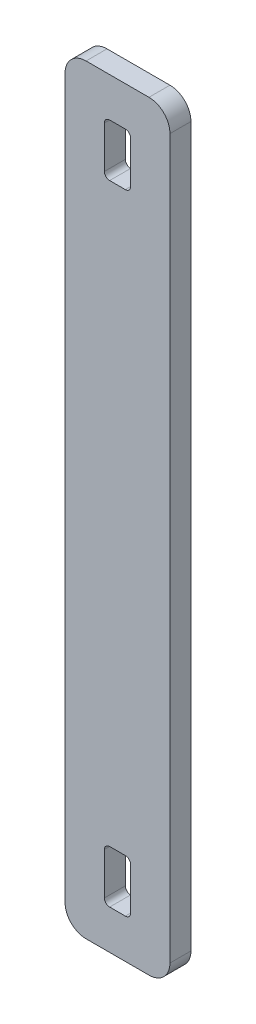
SolidWorks part; units mm, degrees
ref_plane "Plan de face" through (0, 0, 0) normal (0, 0, 1) x (1, 0, 0)
ref_plane "Plan de dessus" through (0, 0, 0) normal (0, 1, 0) x (1, 0, 0)
ref_plane "Plan de droite" through (0, 0, 0) normal (1, 0, 0) x (0, 0, -1)
sketch "Esquisse1" plane through (0, 0, 0) normal (0, 0, 1) x (1, 0, 0)
  line L1 (-6, -72.5) -> (6, -72.5)
  line L2 (-10, -68.5) -> (-10, 68.5)
  line L3 (-6, 72.5) -> (6, 72.5)
  line L4 (10, -68.5) -> (10, 68.5)
  line L5 (-10, -72.5) -> (10, 72.5) construction
  line L6 (-10, 72.5) -> (10, -72.5) construction
  arc A0 (-6, -72.5) -> (-10, -68.5) centre (-6, -68.5) cw
  arc A1 (6, -72.5) -> (10, -68.5) centre (6, -68.5) ccw
  arc A2 (-10, 68.5) -> (-6, 72.5) centre (-6, 68.5) cw
  arc A3 (6, 72.5) -> (10, 68.5) centre (6, 68.5) cw
  point P0 (0, 0)
  dimension "D3" = 4
  dimension "D1" = 145
  dimension "D2" = 20
extrude "Boss.-Extru.1" add sketch "Esquisse1" along normal blind 4
sketch "Esquisse2" plane through (0, 0, 4) normal (0, 0, 1) x (1, 0, 0)
  line L1 (-2.5, -64) -> (-2.5, -56)
  line L2 (-1.5, -65) -> (1.5, -65)
  line L3 (2.5, -64) -> (2.5, -56)
  line L4 (-1.5, -55) -> (1.5, -55)
  line L5 (-2.5, -65) -> (2.5, -55) construction
  line L6 (2.5, -65) -> (-2.5, -55) construction
  line L7 (-2.5, 56) -> (-2.5, 64)
  line L8 (-1.5, 55) -> (1.5, 55)
  line L9 (2.5, 56) -> (2.5, 64)
  line L10 (-1.5, 65) -> (1.5, 65)
  line L11 (-2.5, 55) -> (2.5, 65) construction
  line L12 (2.5, 55) -> (-2.5, 65) construction
  line L13 (10, -68.5) -> (10, 68.5) construction
  line L21 (6, 72.5) -> (-6, 72.5) construction
  line L22 (-6, -72.5) -> (6, -72.5) construction
  line L23 (-10, 68.5) -> (-10, -68.5) construction
  arc A0 (-2.5, 56) -> (-1.5, 55) centre (-1.5, 56) ccw
  arc A1 (1.5, 55) -> (2.5, 56) centre (1.5, 56) ccw
  arc A2 (2.5, 64) -> (1.5, 65) centre (1.5, 64) ccw
  arc A3 (-2.5, 64) -> (-1.5, 65) centre (-1.5, 64) cw
  arc A4 (-2.5, -64) -> (-1.5, -65) centre (-1.5, -64) ccw
  arc A5 (1.5, -65) -> (2.5, -64) centre (1.5, -64) ccw
  arc A6 (2.5, -56) -> (1.5, -55) centre (1.5, -56) ccw
  arc A7 (-2.5, -56) -> (-1.5, -55) centre (-1.5, -56) cw
  point P0 (0, -60)
  point P5 (0, 60)
  dimension "D9" = 1
  dimension "D10" = 1
  dimension "D2" = 7.5
  dimension "D3" = 5
  dimension "D4" = 5
  dimension "D5" = 10
  dimension "D6" = 7.5
  dimension "D7" = 10
  dimension "D8" = 10
  dimension "D13" = 10
extrude "Enlèv. mat.-Extru.1" cut sketch "Esquisse2" against normal through all
